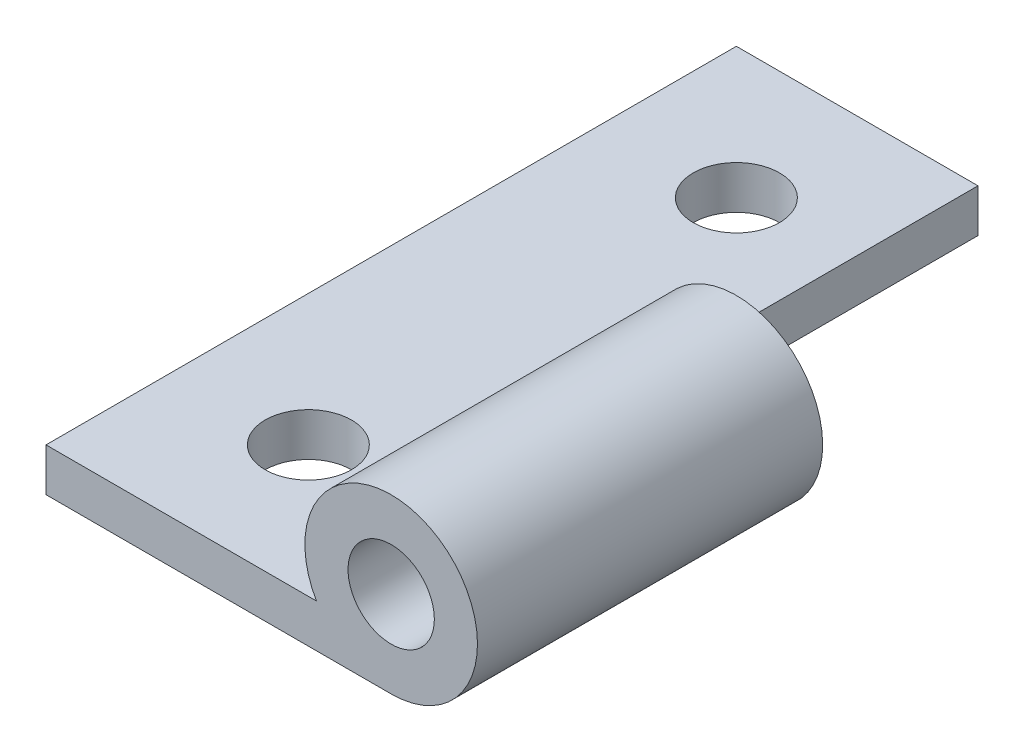
SolidWorks part; units mm, degrees
ref_plane "Front Plane" through (0, 0, 0) normal (0, 0, 1) x (1, 0, 0)
ref_plane "Top Plane" through (0, 0, 0) normal (0, 1, 0) x (1, 0, 0)
ref_plane "Right Plane" through (0, 0, 0) normal (1, 0, 0) x (0, 0, -1)
sketch "Sketch1" plane through (0, 0, 0) normal (0, 0, 1) x (1, 0, 0)
  line L1 (0, 0) -> (-12.7, 0)
  line L2 (0, 0) -> (0, -1.5875)
  line L3 (0, -1.5875) -> (-12.7, -1.5875)
  line L4 (-12.7, 0) -> (-12.7, -1.5875)
  circle A0 centre (0, 1.5875) radius 1.5875
  circle A1 centre (0, 1.5875) radius 3.175
  dimension "D3" = 3.175
  dimension "D1" = 1.5875
  dimension "D2" = 12.7
extrude "Boss-Extrude1" add sketch "Sketch1" along normal blind 12.7 contours A1 L1 L4 L3 | L1 A1 L2 | L2 A1 L1 A0
sketch "Sketch2" plane through (0, 0, 0) normal (0, 0, -1) x (-1, 0, 0)
  line L0 (0, -1.5875) -> (12.7, -1.5875) construction
  line L1 (12.7, 0) -> (3.81, 0)
  line L2 (12.7, 0) -> (12.7, -1.5875)
  line L3 (12.7, -1.5875) -> (3.81, -1.5875)
  line L4 (3.81, 0) -> (3.81, -1.5875)
  dimension "D1" = 8.89
extrude "Boss-Extrude2" add sketch "Sketch2" along normal blind 12.7
sketch "Sketch3" plane through (0, 0, 0) normal (0, 1, 0) x (1, 0, 0)
  line L0 (-12.7, 12.7) -> (-3.81, 12.7) construction
  line L1 (-12.7, -12.7) -> (-12.7, 12.7) construction
  line L2 (-2.7496, -12.7) -> (-12.7, -12.7) construction
  circle A0 centre (-7.874, 7.874) radius 1.5875
  circle A1 centre (-7.874, -7.874) radius 1.5875
  point P10 (-26.2689, -10.1514)
  dimension "D1" = 3.175
  dimension "D2" = 3.175
  dimension "D3" = 4.826
  dimension "D4" = 4.826
  dimension "D5" = 4.826
extrude "Cut-Extrude1" cut sketch "Sketch3" against normal blind 17.78
